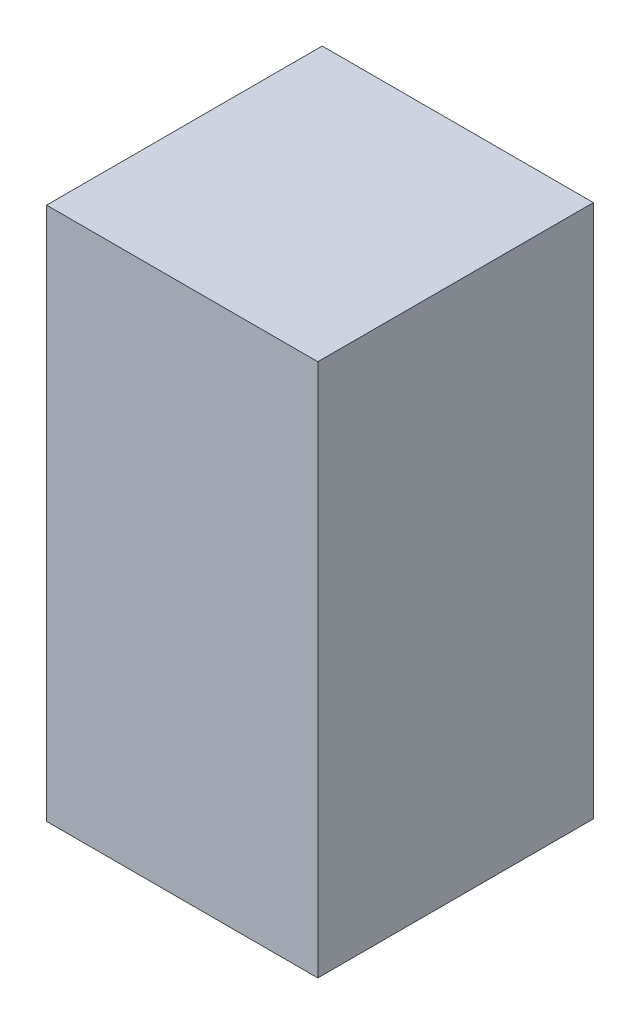
SolidWorks part; units mm, degrees
ref_plane "Front Plane" through (0, 0, 0) normal (1, 0, 0) x (0, 1, 0)
ref_plane "Top Plane" through (0, 0, 0) normal (0, 0, 1) x (0, 1, 0)
ref_plane "Right Plane" through (0, 0, 0) normal (0, 1, 0) x (-1, 0, 0)
sketch "Sketch1" plane through (0, 0, 0) normal (0, 0, 1) x (0, 1, 0)
  line L1 (0, 0) -> (61, 0)
  line L2 (0, 0) -> (0, 31)
  line L3 (0, 31) -> (61, 31)
  line L4 (61, 0) -> (61, 31)
  dimension "D1" = 61
  dimension "D2" = 31
extrude "Boss-Extrude1" add sketch "Sketch1" along normal blind 31.5
